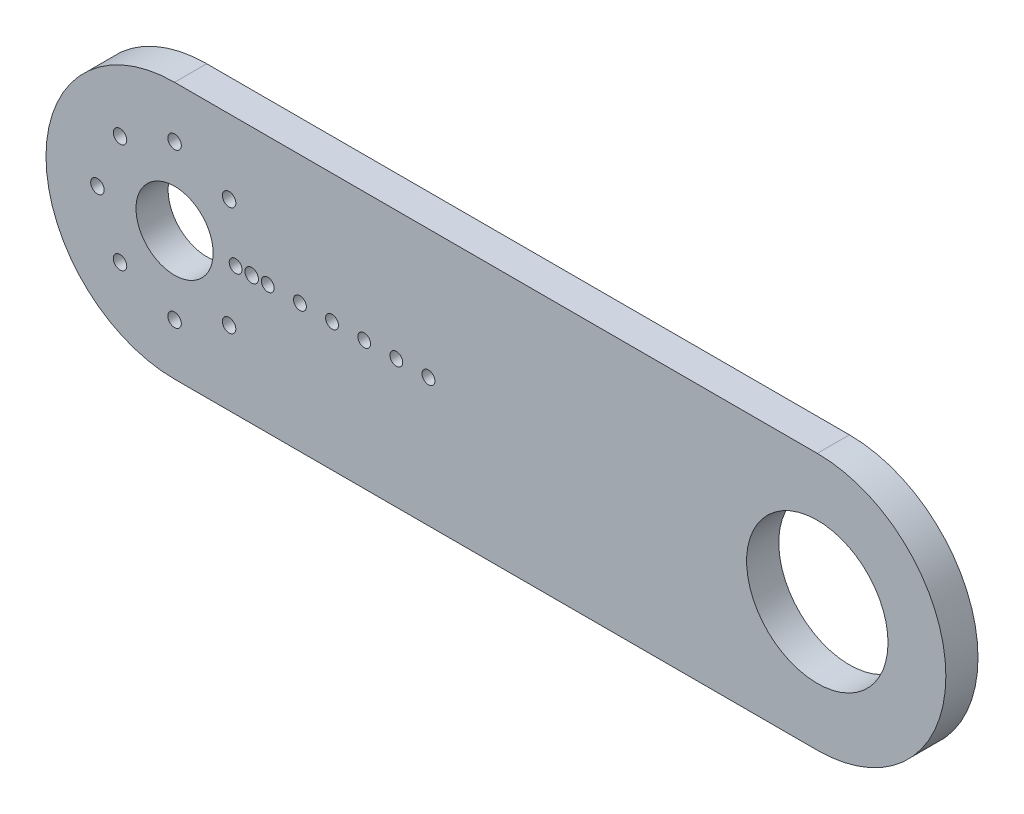
SolidWorks part; units mm, degrees
ref_plane "Front Plane" through (0, 0, 0) normal (0, 0, 1) x (1, 0, 0)
ref_plane "Top Plane" through (0, 0, 0) normal (0, 1, 0) x (1, 0, 0)
ref_plane "Right Plane" through (0, 0, 0) normal (1, 0, 0) x (0, 0, -1)
sketch "Sketch1" plane through (0, 0, 0) normal (0, 0, 1) x (1, 0, 0)
  line L0 (0, 20) -> (100, 20)
  line L1 (55, 0) -> (-55, 0) construction
  line L2 (0, -20) -> (100, -20)
  arc A0 (0, 20) -> (0, -20) centre (0, 0) ccw
  arc A1 (100, -20) -> (100, 20) centre (100, 0) ccw
  arc A2 (0, -20) -> (0, 20) centre (0, 0) ccw construction
  arc A3 (100, 20) -> (100, -20) centre (100, 0) ccw construction
  circle A4 centre (0, 0) radius 6
  circle A5 centre (9.5, 0) radius 1
  circle A6 centre (14.5, 0) radius 1
  circle A7 centre (19.5, 0) radius 1
  circle A8 centre (24.5, 0) radius 1
  circle A9 centre (29.5, 0) radius 1
  circle A10 centre (34.5, 0) radius 1
  circle A11 centre (39.5, 0) radius 1
  circle A12 centre (100, 0) radius 11
  circle A13 centre (0, 0) radius 12 construction
  circle A14 centre (0, 12) radius 1.05
  circle A15 centre (8.4853, 8.4853) radius 1.05
  circle A16 centre (12, 0) radius 1.05
  circle A17 centre (8.4853, -8.4853) radius 1.05
  circle A18 centre (0, -12) radius 1.05
  circle A19 centre (-8.4853, -8.4853) radius 1.05
  circle A20 centre (-12, 0) radius 1.05
  circle A21 centre (-8.4853, 8.4853) radius 1.05
  point P44 (0, 0)
  dimension "D1" = 40
  dimension "D3" = 40
  dimension "D4" = 12
  dimension "D5" = 2
  dimension "D7" = 22
  dimension "D8" = 24
  dimension "D9" = 2.1
  dimension "D2" = 100
  dimension "D6" = 9.5
  dimension "D10" = 8
extrude "Boss-Extrude1" add sketch "Sketch1" along normal mid plane 5
